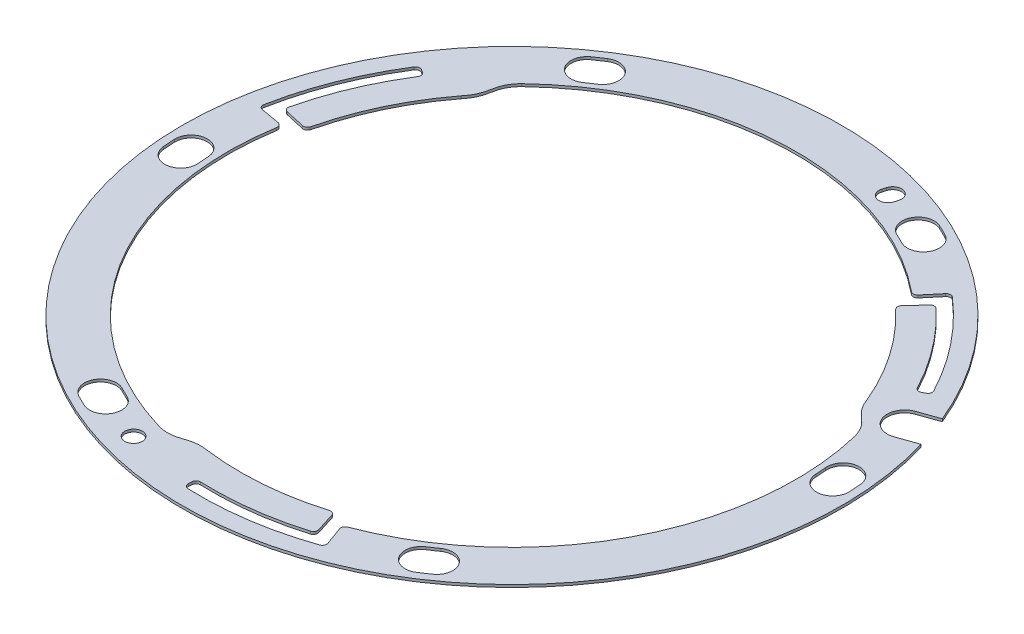
SolidWorks part; units mm, degrees
ref_plane "Front Plane" through (0, 0, 0) normal (0, 0, 1) x (1, 0, 0)
ref_plane "Top Plane" through (0, 0, 0) normal (0, 1, 0) x (1, 0, 0)
ref_plane "Right Plane" through (0, 0, 0) normal (1, 0, 0) x (0, 0, -1)
sketch "Sketch1" plane through (0, 0, 0) normal (0, 1, 0) x (1, 0, 0)
  circle A0 centre (0, 0) radius 38
  dimension "D1" = 76
extrude "Boss-Extrude1" add sketch "Sketch1" along normal blind 0.3
sketch "Sketch2" plane through (0, 0.3, 0) normal (0, 1, 0) x (1, 0, 0)
  line L0 (0, 0) -> (15.4865, 31.6659) construction
  line L1 (0, 0) -> (9.7525, 33.874) construction
  line L2 (9.8148, 34.0903) -> (9.6903, 33.6578) construction
  line L3 (10.7998, 33.8067) -> (10.6753, 33.3742)
  line L4 (8.8298, 34.3738) -> (8.7053, 33.9414)
  line L5 (0, 0) -> (-9.7525, -33.874) construction
  line L6 (-15.4865, -31.6659) -> (0, 0) construction
  line L7 (-19.6802, 29.2447) -> (0, 0) construction
  line L8 (0, 0) -> (-35.1667, -2.4212) construction
  line L9 (0, 0) -> (-33.7787, 7.494) construction
  line L10 (0, 0) -> (-30.1891, 19.6116) construction
  line L11 (-30.1891, 19.6116) -> (-29.0151, 18.849)
  line L12 (-33.7787, 7.494) -> (-30.557, 6.7792)
  line L13 (-35.4521, 6.2568) -> (0, 0) construction
  line L14 (-35.4521, 6.2568) -> (-32.2516, 5.6919)
  line L15 (0, 0) -> (-23.7738, 21.4126) construction
  line L16 (-24.856, 19.0228) -> (-23.252, 20.9427) construction
  line L17 (-23.252, 20.9427) -> (-24.3293, 21.9129) construction
  line L18 (-24.3293, 21.9129) -> (-22.5905, 23.7114) construction
  line L19 (-24.3293, 21.9129) -> (-24.331, 21.9145)
  line L20 (23.1446, 27.5741) -> (21.0551, 25.0847)
  line L21 (32.0787, 16.3387) -> (30.8312, 15.7033)
  line L22 (23.3793, 25.5062) -> (21.1495, 23.0735)
  line L23 (28.9023, 12.0145) -> (29.7629, 9.6655) construction
  line L24 (29.7629, 9.6655) -> (31.1418, 10.1133) construction
  line L25 (31.1418, 10.1133) -> (31.8299, 7.7083) construction
  line L26 (12.3075, -33.8308) -> (11.1964, -30.7766)
  line L27 (-1.8896, -35.9504) -> (-1.8161, -34.5523)
  line L28 (10.3994, -33.0002) -> (9.4075, -29.8528)
  line L29 (-4.0462, -31.0374) -> (-6.5109, -30.6082) construction
  line L30 (-6.5109, -30.6082) -> (-6.8125, -32.0262) construction
  line L31 (-6.8125, -32.0262) -> (-9.2394, -31.4197) construction
  line L32 (0, 0) -> (35.8399, 12.6294) construction
  line L34 (36.4549, 10.7256) -> (34.1467, 9.9122)
  line L35 (35.1255, 14.4982) -> (32.8173, 13.6849)
  circle A0 centre (0, 0) radius 35.25 construction
  arc A1 (14.9, 31.9461) -> (16.0678, 31.375) centre (0, 0) cw construction
  arc A2 (16.9111, 33.0216) -> (15.682, 33.6227) centre (0, 0) ccw
  arc A3 (15.2245, 29.7283) -> (14.118, 30.2695) centre (0, 0) ccw
  arc A4 (15.2245, 29.7283) -> (16.9111, 33.0216) centre (16.0678, 31.375) ccw
  arc A5 (15.682, 33.6227) -> (14.118, 30.2695) centre (14.9, 31.9461) ccw
  arc A6 (35.1161, 3.0693) -> (35.2054, 1.7723) centre (0, 0) cw construction
  arc A7 (37.0531, 1.8654) -> (36.9591, 3.2304) centre (0, 0) ccw
  arc A8 (33.3578, 1.6793) -> (33.2731, 2.9082) centre (0, 0) ccw
  arc A9 (33.3578, 1.6793) -> (37.0531, 1.8654) centre (35.2054, 1.7723) ccw
  arc A10 (36.9591, 3.2304) -> (33.2731, 2.9082) centre (35.1161, 3.0693) ccw
  arc A11 (20.2161, -28.8768) -> (19.1376, -29.6026) centre (0, 0) cw construction
  arc A12 (20.142, -31.1562) -> (21.2771, -30.3923) centre (0, 0) ccw
  arc A13 (18.1332, -28.049) -> (19.1551, -27.3613) centre (0, 0) ccw
  arc A14 (18.1332, -28.049) -> (20.142, -31.1562) centre (19.1376, -29.6026) ccw
  arc A15 (21.2771, -30.3923) -> (19.1551, -27.3613) centre (20.2161, -28.8768) ccw
  arc A16 (-14.9, -31.9461) -> (-16.0678, -31.375) centre (0, 0) cw construction
  arc A17 (-16.9111, -33.0216) -> (-15.682, -33.6227) centre (0, 0) ccw
  arc A18 (-15.2245, -29.7283) -> (-14.118, -30.2695) centre (0, 0) ccw
  arc A19 (-15.2245, -29.7283) -> (-16.9111, -33.0216) centre (-16.0678, -31.375) ccw
  arc A20 (-15.682, -33.6227) -> (-14.118, -30.2695) centre (-14.9, -31.9461) ccw
  arc A21 (-35.1161, -3.0693) -> (-35.2054, -1.7723) centre (0, 0) cw construction
  arc A22 (-37.0531, -1.8654) -> (-36.9591, -3.2304) centre (0, 0) ccw
  arc A23 (-33.3578, -1.6793) -> (-33.2731, -2.9082) centre (0, 0) ccw
  arc A24 (-33.3578, -1.6793) -> (-37.0531, -1.8654) centre (-35.2054, -1.7723) ccw
  arc A25 (-36.9591, -3.2304) -> (-33.2731, -2.9082) centre (-35.1161, -3.0693) ccw
  arc A26 (-20.2161, 28.8768) -> (-19.1376, 29.6026) centre (0, 0) cw construction
  arc A27 (-20.142, 31.1562) -> (-21.2771, 30.3923) centre (0, 0) ccw
  arc A28 (-18.1332, 28.049) -> (-19.1551, 27.3613) centre (0, 0) ccw
  arc A29 (-18.1332, 28.049) -> (-20.142, 31.1562) centre (-19.1376, 29.6026) ccw
  arc A30 (-21.2771, 30.3923) -> (-19.1551, 27.3613) centre (-20.2161, 28.8768) ccw
  arc A31 (10.7998, 33.8067) -> (8.8298, 34.3738) centre (9.8148, 34.0903) ccw
  arc A32 (8.7053, 33.9414) -> (10.6753, 33.3742) centre (9.6903, 33.6578) ccw
  circle A33 centre (-9.7525, -33.874) radius 1.015
  arc A34 (-35.4521, 6.2568) -> (-30.1891, 19.6116) centre (0, 0) cw
  arc A35 (-29.0151, 18.849) -> (-33.7787, 7.494) centre (0, 0) ccw
  arc A36 (-30.557, 6.7792) -> (-24.856, 19.0228) centre (0, 0) cw
  circle A37 centre (0, 0) radius 38 construction
  arc A38 (-32.2516, 5.6919) -> (-9.0609, -31.4716) centre (0, 0) ccw
  arc A39 (23.1446, 27.5741) -> (32.0787, 16.3387) centre (0, 0) cw
  arc A40 (30.8312, 15.7033) -> (23.3793, 25.5062) centre (0, 0) ccw
  arc A41 (21.1495, 23.0735) -> (28.9023, 12.0145) centre (0, 0) cw
  arc A42 (12.3075, -33.8308) -> (-1.8896, -35.9504) centre (0, 0) cw
  arc A43 (-1.8161, -34.5523) -> (10.3994, -33.0002) centre (0, 0) ccw
  arc A44 (9.4075, -29.8528) -> (-4.0462, -31.0374) centre (0, 0) cw
  arc A45 (21.0551, 25.0847) -> (-22.5905, 23.7114) centre (0, 0) ccw
  arc A46 (11.1964, -30.7766) -> (31.8299, 7.7083) centre (0, 0) ccw
  arc A48 (32.8173, 13.6849) -> (34.1467, 9.9122) centre (33.482, 11.7986) ccw
  arc A49 (35.1255, 14.4982) -> (36.4549, 10.7256) centre (0, 0) cw
  spline S0 degree 3 poles (-24.856, 19.0228) (-23.252, 20.9427) (-24.3293, 21.9129) (-22.5905, 23.7114) knots 0 0 0 0 1 1 1 1
  spline S1 degree 3 poles (28.9023, 12.0145) (29.7629, 9.6655) (31.1418, 10.1133) (31.8299, 7.7083) knots 0 0 0 0 1 1 1 1
  spline S2 degree 3 poles (-4.0462, -31.0374) (-6.5109, -30.6082) (-6.8125, -32.0262) (-9.2394, -31.4197) knots 0 0 0 0 1 1 1 1
  point P6 (15.4865, 31.6659)
  point P16 (35.1667, 2.4212)
  point P23 (19.6802, -29.2447)
  point P30 (-15.4865, -31.6659)
  point P37 (-35.1667, -2.4212)
  point P44 (-19.6802, 29.2447)
  point P49 (0, 0)
  point P51 (9.7525, 33.874)
  point P56 (10.0984, 35.0752)
  point P57 (9.4067, 32.6728)
  point P80 (0, 0)
  point P103 (35.8399, 12.6294)
  point P104 (0, 0)
  point P105 (31.5957, 11.1338)
  point P107 (34.955, 4.9122)
  point P111 (49.5847, 8.316)
  point P112 (0, 0)
  point P113 (0, 0)
  point P114 (0, 0)
  dimension "D2" = 3.7
  dimension "D9" = 2.03
  dimension "D10" = 2
  dimension "D11" = 1.4
  dimension "D12" = 3.3
  dimension "D13" = 65.5
  dimension "D14" = 70.5
  dimension "D23" = 5
  dimension "D3" = 1.3
  dimension "D5" = 2.05
  dimension "D6" = 2.5
  dimension "D7" = 10
  dimension "D8" = 10
  dimension "D15" = 23
  dimension "D16" = 2.5
  dimension "D17" = 9
  dimension "D18" = 2.5
  dimension "D19" = 2.5
  dimension "D21" = 4
  dimension "D22" = 4.5
  dimension "D24" = 2.7
  dimension "D4" = 6
  dimension "D20" = 3
extrude "Cut-Extrude1" cut sketch "Sketch2" against normal through all and the other way through all contours A22 A25 A23 A24 | A17 A20 A18 A19 | A33 | A12 A15 A13 A14 | A7 A10 A8 A9 | A2 A5 A3 A4 | A27 A30 A28 A29 | S2 A44 L28 A43 L27 A42 L26 A46 S1 A41 L22 A40 L21 A39 L20 A45 S0 A36 L12 A35 L11 A34 L14 A38 | L34 A48 L35 A49 | A31 L4 A32 L3
fillet "Fillet2" radius 0.5 24 edges at (-9.2394, 0.15, 31.4197) (-35.4521, 0.15, -6.2568) (-30.1891, 0.15, -19.6116) (-29.0151, 0.15, -18.849) (-33.7787, 0.15, -7.494) (-30.557, 0.15, -6.7792) (-24.856, 0.15, -19.0228) (-22.5905, 0.15, -23.7114) (21.0551, 0.15, -25.0847) (23.1446, 0.15, -27.5741) (32.0787, 0.15, -16.3387) (30.8312, 0.15, -15.7033) (23.3793, 0.15, -25.5062) (21.1495, 0.15, -23.0735) (28.9023, 0.15, -12.0145) (31.8299, 0.15, -7.7083) (11.1964, 0.15, 30.7766) (12.3075, 0.15, 33.8308) (-1.8896, 0.15, 35.9504) (-1.8161, 0.15, 34.5523) (10.3994, 0.15, 33.0002) (9.4075, 0.15, 29.8528) (-4.0462, 0.15, 31.0374) (-32.2516, 0.15, -5.6919)
